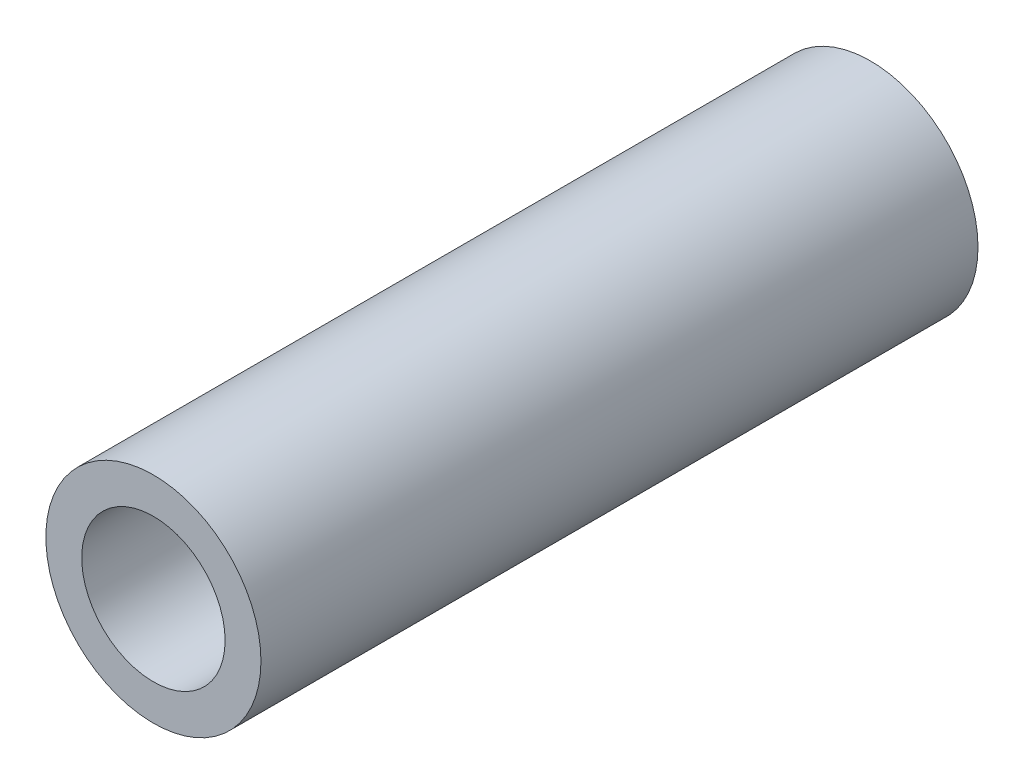
SolidWorks part; units mm, degrees
material "PF"
ref_plane "Front Plane" through (0, 0, 0) normal (0, 0, 1) x (1, 0, 0)
ref_plane "Top Plane" through (0, 0, 0) normal (0, 1, 0) x (1, 0, 0)
ref_plane "Right Plane" through (0, 0, 0) normal (1, 0, 0) x (0, 0, -1)
sketch "Sketch1" plane through (0, 0, 0) normal (0, 0, 1) x (1, 0, 0)
  circle A0 centre (0, 0) radius 5
sketch "Sketch2" plane through (0, 0, 0) normal (0, 0, 1) x (1, 0, 0)
  circle A0 centre (0, 0) radius 7.5
ref_plane "Plane1" through (0, 0, 50) normal (0, 0, 1) x (1, 0, 0)
sketch "Sketch3" plane through (0, 0, 50) normal (0, 0, 1) x (1, 0, 0)
  circle A0 centre (0, 0) radius 7.5
loft "Loft1" add profiles "Sketch3", "Sketch2"
extrude "Cut-Extrude1" cut sketch "Sketch1" along normal blind 61 contours A0
